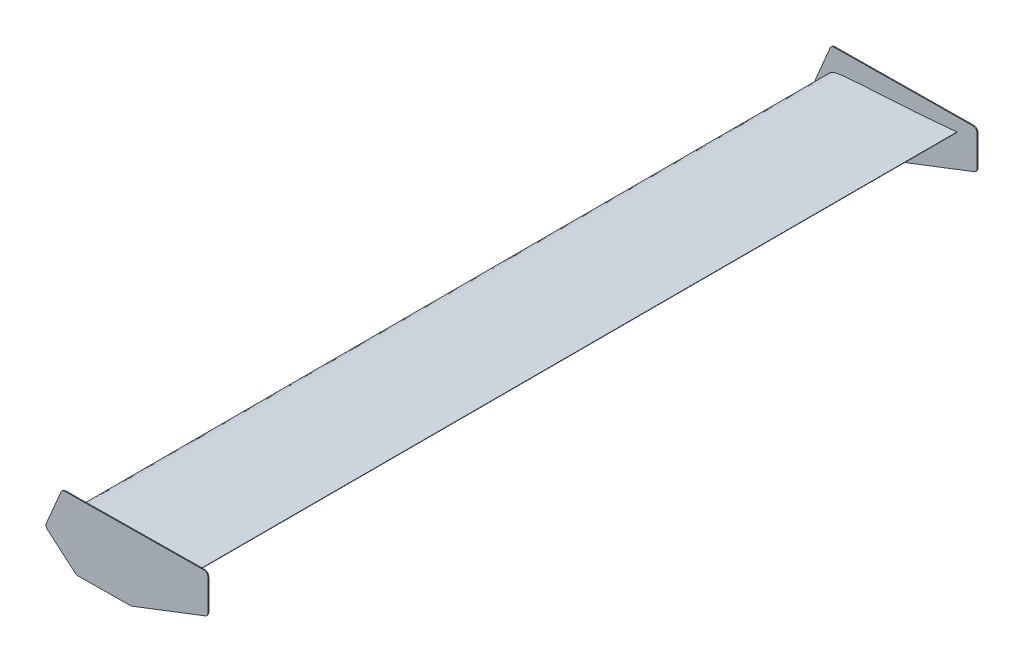
SolidWorks part; units mm, degrees
ref_plane "Front Plane" through (0, 0, 0) normal (0, 0, 1) x (1, 0, 0)
ref_plane "Top Plane" through (0, 0, 0) normal (0, 1, 0) x (1, 0, 0)
ref_plane "Right Plane" through (0, 0, 0) normal (1, 0, 0) x (0, 0, -1)
curve "Airfoil Curve"
  spline degree 3 poles (300, -0.39, 0) (295.0052, -1.7497, 0) (285.0396, -4.4626, 0) (265.0756, -9.3952, 0) (240.11, -14.8452, 0) (210.0811, -20.2176, 0) (180.0755, -24.6212, 0) (150.0532, -27.7624, 0) (120.0335, -29.7214, 0) (94.9726, -29.7413, 0) (74.963, -28.3569, 0) (59.9355, -26.5335, 0) (44.8755, -23.8445, 0) (32.3958, -20.6106, 0) (22.3952, -17.3445, 0) (14.8545, -14.2611, 0) (8.4203, -10.9265, 0) (2.8355, -6.9378, 0) (-2.0261, -0.5226, 0) (3.2214, 4.3836, 0) (8.5759, 6.3095, 0) (14.9528, 7.6093, 0) (22.4839, 8.2702, 0) (32.4958, 8.738, 0) (45.0031, 8.7029, 0) (60.0065, 8.2831, 0) (74.9993, 7.4837, 0) (94.9994, 6.5483, 0) (119.9952, 5.3479, 0) (150.0009, 4.2208, 0) (179.9969, 2.9692, 0) (209.9958, 1.9031, 0) (239.9971, 1.119, 0) (264.9992, 0.7209, 0) (284.9995, 0.4587, 0) (294.9999, 0.4129, 0) (300, 0.39, 0) knots 0 0 0 0 0.025305 0.050488 0.10052 0.150191 0.199587 0.24874 0.297716 0.346601 0.371103 0.395726 0.42057 0.445825 0.458702 0.47192 0.485786 0.493461 0.506863 0.516148 0.522766 0.535269 0.547551 0.559786 0.584229 0.608681 0.633151 0.657622 0.706558 0.755482 0.804406 0.85332 0.902221 0.951113 0.975557 1 1 1 1
ref_plane "Plane1" through (300, -0.39, 0) normal (-0.9649, -0.2627, 0) x (0, 0, 1)
sketch "AirfoilSketch" plane through (0, 0, 0) normal (0, 0, 1) x (1, 0, 0)
  line L2 (0, 0) -> (350.3559, 0) construction
  line B0 (298.3568, 31.3586) -> (298.4373, 30.5827)
  line B1 (0, 0) -> (298.3568, 31.3586) construction
  spline B2 degree 3 poles (298.4373, 30.5827) (293.6096, 28.7146) (283.9773, 24.9875) (264.6292, 18.0202) (240.3596, 10.022) (211.0458, 1.5783) (181.6551, -5.8995) (152.1175, -12.1232) (122.4604, -17.1709) (97.5356, -19.7778) (77.4899, -20.4666) (62.3544, -20.2043) (47.0973, -19.0844) (34.3505, -17.1561) (24.0661, -14.9398) (16.2474, -12.6514) (9.5034, -9.9989) (3.5366, -6.608) (-1.9613, -0.729) (2.7516, 4.6927) (7.8787, 7.1611) (14.0874, 9.1123) (21.51, 10.5472) (31.4201, 12.046) (43.8642, 13.3023) (58.8308, 14.4336) (73.826, 15.1863) (93.8158, 16.3206) (118.802, 17.7071) (148.7637, 19.6836) (178.7286, 21.5354) (208.6773, 23.572) (238.5992, 25.8892) (263.5089, 28.0743) (283.4294, 29.8783) (293.3811, 30.8652) (298.3568, 31.3586) knots 0 0 0 0 0.025305 0.050488 0.10052 0.150191 0.199587 0.24874 0.297716 0.346601 0.371103 0.395726 0.42057 0.445825 0.458702 0.47192 0.485786 0.493461 0.506863 0.516148 0.522766 0.535269 0.547551 0.559786 0.584229 0.608681 0.633151 0.657622 0.706558 0.755482 0.804406 0.85332 0.902221 0.951113 0.975557 1 1 1 1
  dimension "AoA_Rear_Wing" = 6
sketch_block_instance "AirfoilBlock-1"
sketch_block "AirfoilBlock"
extrude "Rear Wing" add sketch "AirfoilSketch" along normal mid plane 1800
sketch "Endplate Sketch" plane through (0, 0, 900) normal (0, 0, 1) x (1, 0, 0)
  line L0 (4.1984, 59.4067) -> (-35.2909, -33.8505)
  line L1 (-35.2909, -33.8505) -> (38.2575, -96.7338)
  line L2 (4.1984, 59.4067) -> (345.6673, 62.9082)
  line L3 (345.6673, 62.9082) -> (345.6673, -26.3186)
  line L5 (38.2575, -96.7338) -> (166.2751, -95.4211)
  line L6 (166.2751, -95.4211) -> (345.6673, -26.3186)
  point P2 (152.1224, -101.9226)
  point P6 (313.3454, 63.1358)
  point P7 (345.6673, -26.3186)
  point P8 (345.6673, 62.9082)
  point P9 (4.1984, 59.4067)
  point P10 (-35.2909, -33.8505)
extrude "Endplate" add sketch "Endplate Sketch" along normal mid plane 2
fillet "Endplate Fillet" radius 10 6 edges at (345.6673, 62.9082, 900) (345.6673, -26.3186, 900) (166.2751, -95.4211, 900) (4.1984, 59.4067, 900) (-35.2909, -33.8505, 900) (38.2575, -96.7338, 900)
mirror "Mirror3" about plane through (0, 0, 0) normal (0, 0, 1) of "Endplate Fillet", "Endplate"
